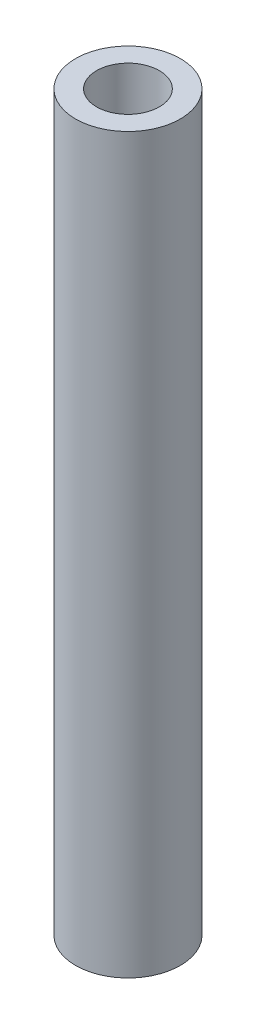
SolidWorks part; units mm, degrees
ref_plane "Front Plane" through (0, 0, 0) normal (0, 0, 1) x (1, 0, 0)
ref_plane "Top Plane" through (0, 0, 0) normal (0, 1, 0) x (1, 0, 0)
ref_plane "Right Plane" through (0, 0, 0) normal (1, 0, 0) x (0, 0, -1)
sketch "Sketch1" plane through (0, 0, 0) normal (0, 1, 0) x (1, 0, 0)
  circle A0 centre (0, 0) radius 2.5
  circle A1 centre (0, 0) radius 1.5
  dimension "D1" = 3
  dimension "D2" = 5
extrude "Boss-Extrude1" add sketch "Sketch1" along normal blind 35
